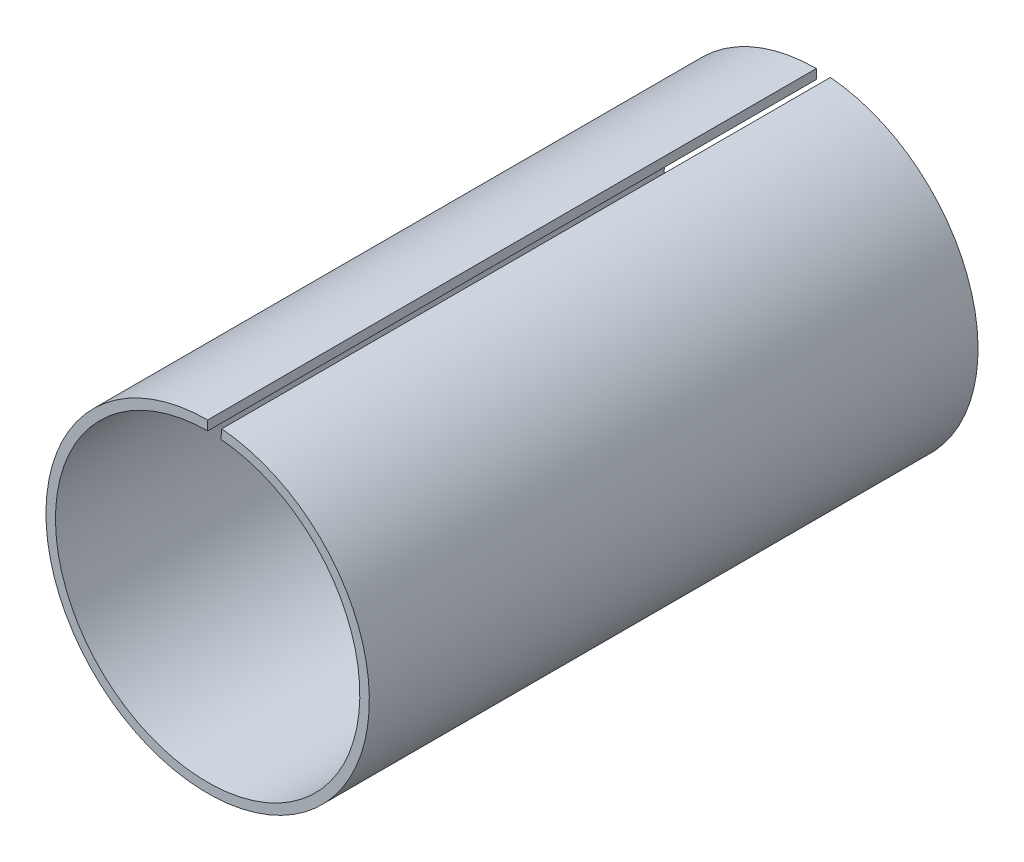
SolidWorks part; units mm, degrees
material "BUTYL"
ref_plane "Front" through (0, 0, 0) normal (0, 0, 1) x (1, 0, 0)
ref_plane "Top" through (0, 0, 0) normal (0, 1, 0) x (1, 0, 0)
ref_plane "Right" through (0, 0, 0) normal (1, 0, 0) x (0, 0, -1)
sketch "Sketch1" plane through (0, 0, 0) normal (0, 0, 1) x (1, 0, 0)
  circle A0 centre (0, 0) radius 13.4938
  circle A1 centre (0, 0) radius 12.7
  dimension "D1" = 26.9875
  dimension "D2" = 25.4
extrude "Boss-Extrude1" add sketch "Sketch1" along normal blind 50.8
sketch "Sketch2" plane through (0, 0, 50.8) normal (0, 0, 1) x (1, 0, 0)
  line L0 (0, 0) -> (0, 13.4937)
  line L1 (0, 0) -> (1.1761, 13.4424)
  circle A0 centre (0, 0) radius 13.4937 construction
  arc A1 (1.1761, 13.4424) -> (0, 13.4937) centre (0, 0) ccw
  dimension "D1" = 5
extrude "Cut-Extrude1" cut sketch "Sketch2" against normal through all
